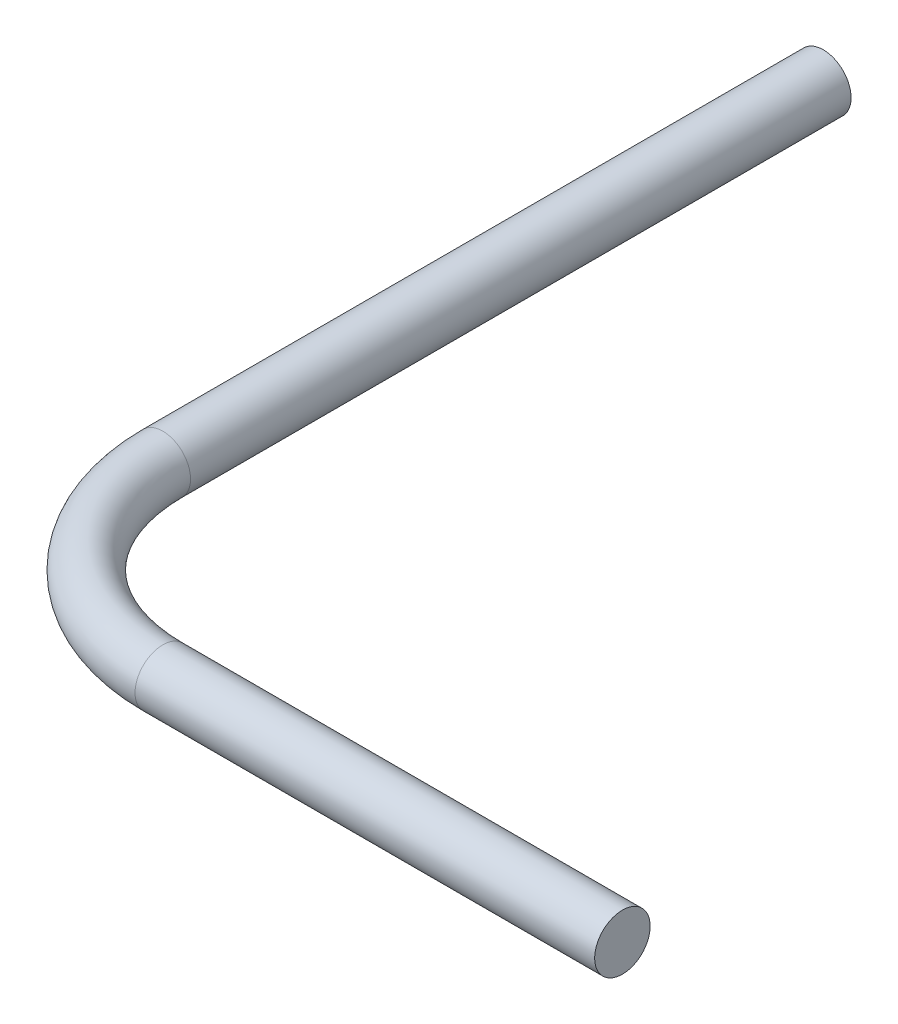
SolidWorks part; units mm, degrees
ref_plane "Alzado" through (0, 0, 0) normal (0, 0, 1) x (1, 0, 0)
ref_plane "Planta" through (0, 0, 0) normal (0, 1, 0) x (1, 0, 0)
ref_plane "Vista lateral" through (0, 0, 0) normal (1, 0, 0) x (0, 0, -1)
sketch "Croquis2" plane through (0, 0, 0) normal (0, 1, 0) x (1, 0, 0)
  line L0 (0, 0) -> (-24.84, 0)
  line L1 (-34.84, 10) -> (-34.84, 45.7)
  arc A0 (-24.84, 0) -> (-34.84, 10) centre (-24.84, 10) cw
  point P6 (-34.84, 0)
  dimension "D3" = 10
  dimension "D1" = 34.84
  dimension "D2" = 45.7
sweep "Barrer1" add path "Croquis2" circular profile diameter 3 parameters "D3"=3
